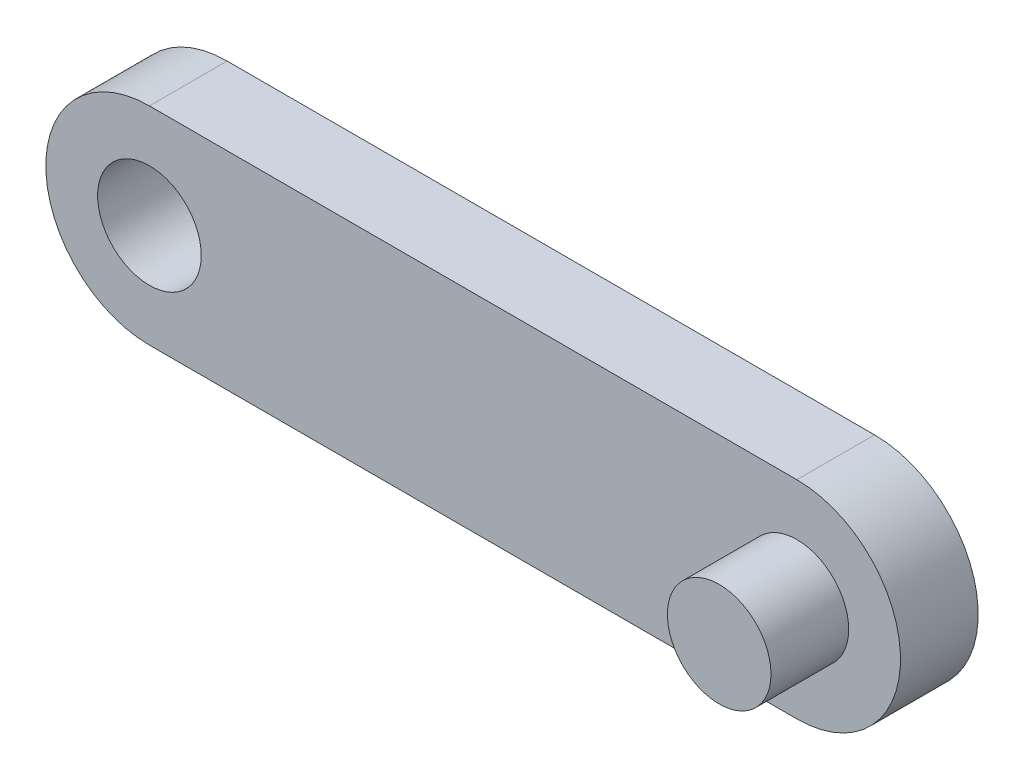
SolidWorks part; units mm, degrees
ref_plane "Front Plane" through (0, 0, 0) normal (0, 0, 1) x (1, 0, 0)
ref_plane "Top Plane" through (0, 0, 0) normal (0, 1, 0) x (1, 0, 0)
ref_plane "Right Plane" through (0, 0, 0) normal (1, 0, 0) x (0, 0, -1)
sketch "Sketch2" plane through (0, 0, 0) normal (0, 0, 1) x (1, 0, 0)
  line L4 (0, 0) -> (250, 0)
  line L6 (0, -80) -> (250, -80)
  arc A0 (0, 0) -> (0, -80) centre (0, -40) ccw
  arc A1 (250, -80) -> (250, 0) centre (250, -40) ccw
  circle A3 centre (0, -40) radius 20
  dimension "D3" = 40
  dimension "D4" = 80
  dimension "D1" = 250
extrude "Boss-Extrude1" add sketch "Sketch2" along normal blind 30
sketch "Sketch6" plane through (0, 0, 30) normal (0, 0, 1) x (1, 0, 0)
  point P0 (0, -40)
sketch "Sketch7" plane through (0, 0, 30) normal (0, 0, 1) x (1, 0, 0)
  circle A0 centre (250, -40) radius 20
  dimension "D1" = 40
extrude "Boss-Extrude2" add sketch "Sketch7" along normal blind 30
